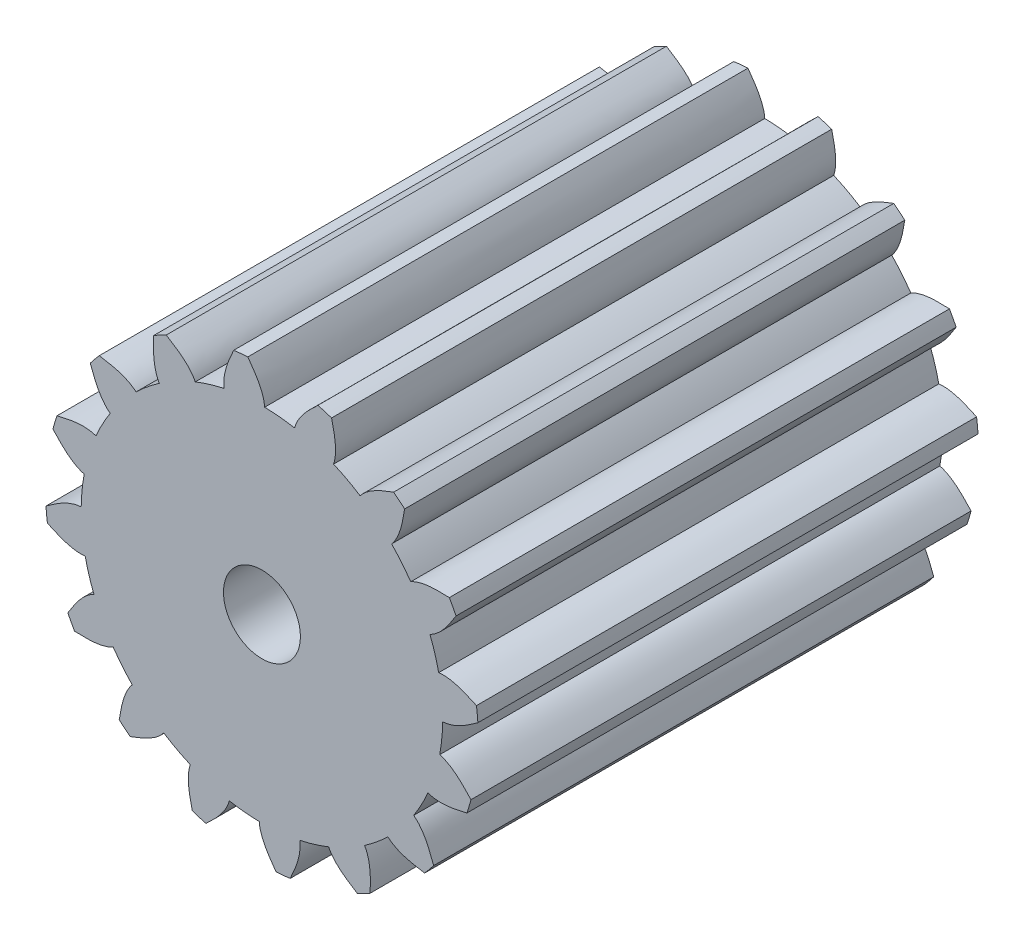
SolidWorks part; units mm, degrees
ref_plane "Front Plane" through (0, 0, 0) normal (0, 0, 1) x (1, 0, 0)
ref_plane "Top Plane" through (0, 0, 0) normal (0, 1, 0) x (1, 0, 0)
ref_plane "Right Plane" through (0, 0, 0) normal (1, 0, 0) x (0, 0, -1)
sketch "punti involuta" plane through (0, 0, 0) normal (0, 0, 1) x (1, 0, 0)
  line L0 (0, 0) -> (0, 4.6277) construction
  line L1 (-3.4916, 2) -> (3.4916, 2) construction
  line L2 (-3.4916, 0.7292) -> (3.4916, 3.2708) construction
  line L3 (0, 0) -> (-0.6428, 1.766) construction
  line L4 (-0.6428, 1.766) -> (0, 2) construction
  line L5 (-1.2414, 1.411) -> (-0.2023, 2.3252) construction
  line L6 (-0.3539, 1.8458) -> (0.0233, 1.9181) construction
  circle A0 centre (0, 0) radius 2 construction
  circle A1 centre (0, 0) radius 1.8794 construction
  arc A2 (-0.6428, 1.766) -> (-1.2414, 1.411) centre (0, 0) ccw construction
  arc A3 (-0.6428, 1.766) -> (-0.3539, 1.8458) centre (0, 0) cw construction
  arc A4 (-0.6428, 1.766) -> (0.028, 1.8792) centre (0, 0) cw construction
  point P4 (0, 2)
  point P7 (0, 2)
  dimension "D1" = 4
  dimension "D2" = 20
  dimension "D3" = 0.684
  dimension "D5" = 1.384
  dimension "D7" = 0.384
  dimension "D4" = 0.7
  dimension "D6" = 0.3
  dimension "D8" = 0.684
sketch "diametro testa" plane through (0, 0, 0) normal (0, 0, 1) x (1, 0, 0)
  circle A0 centre (0, 0) radius 2.25
  dimension "D1" = 4.5
sketch "profilo" plane through (0, 0, 0) normal (0, 0, 1) x (1, 0, 0)
  line L0 (0, 0) -> (-0.1842, 1.8703) construction
  line L1 (0, 0) -> (0, 4.6277) construction
  line L2 (-0.1842, 1.8703) -> (-0.2205, 2.2392)
  arc A1 (-0.2205, 2.2392) -> (-0.1467, 2.2452) centre (0, 0) cw
  circle A3 centre (0, 0) radius 2.25 construction
  arc A4 (0.028, 1.8792) -> (-0.1842, 1.8703) centre (0, 0) ccw
  arc A5 (0.028, 1.8792) -> (-0.6428, 1.766) centre (0, 0) ccw construction
  circle A6 centre (0, 0) radius 1.8794 construction
  spline S0 degree 3 poles (-0.2023, 2.3252) (-0.1183, 2.1969) (0.0168, 2.0487) (0.028, 1.8792) knots 0 0 0 0 1 1 1 1
  dimension "D1" = 5.625
sketch "diametro base" plane through (0, 0, 0) normal (0, 0, 1) x (1, 0, 0)
  circle A0 centre (0, 0) radius 1.8794
extrude "Boss-Extrude7" add sketch "profilo" along normal blind 5.2 contours S0 A1 L2 A4
ref_plane "Plane1" through (0, 0, 0) normal (0.9952, 0.098, 0) x (-0.098, 0.9952, 0)
mirror "Mirror1" about plane through (0, 0, 0) normal (0.9952, 0.098, 0) of bodies 112
pattern_circular "CirPattern1" count 16 over 360 about axis through (0, 0, 5.2) along (0, 0, 1) of bodies 113
extrude "Boss-Extrude9" add sketch "diametro base" along normal up to surface (5.2 mm away)
sketch "mozzo" plane through (0, 0, 0) normal (0, 0, 1) x (1, 0, 0)
  circle A0 centre (0, 0) radius 0.4
  dimension "D1" = 0.8
extrude "Cut-Extrude1" cut sketch "mozzo" along normal up to surface (5.2 mm away) up to face at (0, 0, 5.2)
equation "\"n_imposto\"= 16"
equation "\"m\"= .25"
equation "\"d_imposto\"= \"n_imposto\" * \"m\""
equation "\"alpha\"= 20"
equation "\"a1\"= .7"
equation "\"a2\"= .3"
equation "\"s\"= 5.2"
equation "\"D1@punti involuta\"=\"d_imposto\""
equation "\"D2@punti involuta\" = \"alpha\""
equation "\"D4@punti involuta\" = \"a1\""
equation "\"D5@punti involuta\" = \"D3@punti involuta\" + \"a1\""
equation "\"D6@punti involuta\" = \"a2\""
equation "\"D7@punti involuta\" = \"D3@punti involuta\" - \"a2\""
equation "\"D1@diametro testa\"=\"d_imposto\" + \"m\" * 2"
equation "\"D8@punti involuta\"=\"D3@punti involuta\""
equation "\"D1@profilo\"=360 / \"n_imposto\" / 4"
equation "\"D1@Boss-Extrude7\"=\"s\""
equation "\"D1@CirPattern1\"= \"n_imposto\""
equation "\"d_mozzo\"= .8"
equation "\"D1@mozzo\"=\"d_mozzo\""
